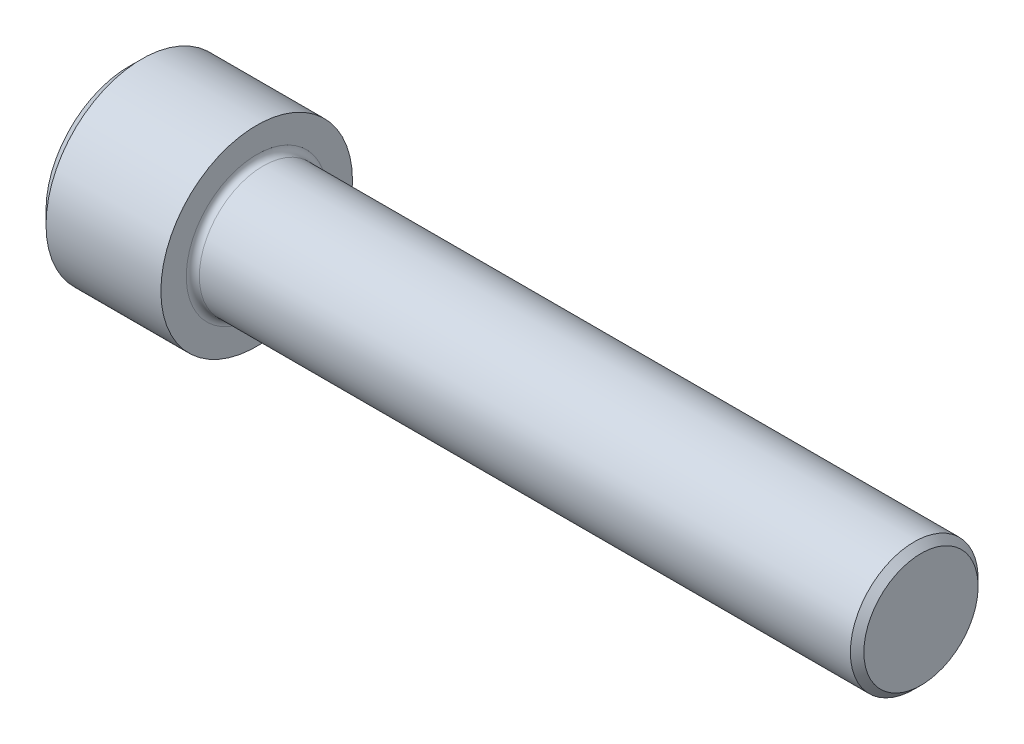
SolidWorks part; units mm, degrees
ref_plane "Plane1" through (0, 0, 0) normal (0, 0, 1) x (1, 0, 0)
ref_plane "Plane2" through (0, 0, 0) normal (0, 1, 0) x (1, 0, 0)
ref_plane "Plane3" through (0, 0, 0) normal (1, 0, 0) x (0, 0, -1)
sketch "BodySke" plane through (0, 0, 0) normal (0, 0, 1) x (1, 0, 0)
  line L0 (0, 0) -> (0, 10.3061)
  line L1 (1.6002, 11.9062) -> (15.875, 11.9062)
  line L2 (15.875, 11.9062) -> (15.875, 7.9375)
  line L3 (15.875, 7.9375) -> (97.5855, 7.9375)
  line L4 (98.425, 7.098) -> (98.425, 0)
  line L5 (98.425, 0) -> (0, 0)
  line L6 (-31.75, 0) -> (127, 0) construction
  line L7 (0, 10.3061) -> (1.6002, 11.9062)
  line L8 (98.425, 7.098) -> (97.5855, 7.9375)
  line L9 (0, -10.3061) -> (1.6002, -11.9063) construction
  line L10 (98.425, -7.098) -> (97.5855, -7.9375) construction
  line L11 (17.2847, 9.525) -> (17.2847, 3.175) construction
  line L12 (53.975, 9.525) -> (53.975, 3.175) construction
  line L13 (60.325, 9.525) -> (60.325, 3.175) construction
  dimension "Diameter" = 15.875
  dimension "Head_ht" = 15.875
  dimension "Length" = 82.55
  dimension "Body_ch_ang" = 45
  dimension "Head_dia" = 23.8125
  dimension "Head_ch_ang" = 45
  dimension "Head_side_ht" = 14.2748
  dimension "Minor_dia" = 14.1961
  dimension "Advance" = 1.4097
  dimension "Thread_nom" = 44.45
  dimension "Thread_length" = 38.1
revolve "Base-Revolve" add sketch "BodySke"
cosmetic thread "ThreadCosmetic" [suppressed]
fillet "Fillet1" radius 0.8128 1 edges at (15.875, 0, 7.9375)
sketch "Sketch2" plane through (0, 0, 0) normal (0, 0, 1) x (1, 0, 0)
  line L0 (0, 6.35) -> (7.7978, 6.35)
  line L1 (7.7978, 6.35) -> (11.464, 0)
  line L2 (-31.75, 0) -> (127, 0) construction
  line L3 (11.464, 0) -> (0, 0)
  line L4 (0, 0) -> (0, 6.35)
  line L5 (0, 10.3061) -> (0, -10.3061) construction
  line L6 (0, 0) -> (47.625, 0) construction
  line L7 (15.875, -11.9062) -> (15.875, 11.9062) construction
  dimension "D1" = 6.35
  dimension "D2" = 60
  dimension "Wall_thickness" = 8.0772
revolve "Hex-PreBroach" cut sketch "Sketch2" angle 360 about L6
sketch "Sketch3" plane through (0, 0, 0) normal (-1, 0, 0) x (0, 0.5, 0.866)
  line L0 (3.6662, 6.35) -> (-3.6662, 6.35)
  line L1 (-3.6662, 6.35) -> (-7.3323, 0)
  line L2 (3.6662, 6.35) -> (7.3323, 0)
  line L3 (3.6662, -6.35) -> (7.3323, 0)
  line L4 (3.6662, -6.35) -> (-3.6662, -6.35)
  line L5 (-3.6662, -6.35) -> (-7.3323, 0)
  dimension "D1" = 6.35
  dimension "D2" = 6.35
  dimension "Hex_size" = 12.7
extrude "Hex" cut sketch "Sketch3" against normal blind 7.7978
sketch "Sketch4" plane through (0, 0, 0) normal (-1, 0, 0) x (0, 0, 1)
  line L0 (0, 0) -> (7.6708, 0)
  line L1 (0, 0) -> (6.1484, 3.5498) construction
  line L2 (0, 0) -> (3.8354, 6.6431)
  line L3 (6.2649, 1.5933) -> (7.3437, 2.2162)
  line L4 (4.5123, 4.6289) -> (5.5911, 5.2517)
  arc A0 (6.2649, 1.5933) -> (4.5123, 4.6289) centre (0, 0) ccw
  arc A1 (7.6708, 0) -> (7.3437, 2.2162) centre (0, 0) ccw
  arc A2 (3.8354, 6.6431) -> (5.5911, 5.2517) centre (0, 0) cw
  dimension "D1" = 30
  dimension "Spline_n_dim" = 12.9286
  dimension "Spline_m_dim" = 15.3416
  dimension "D2" = 60
  dimension "D3" = 1.7526
  dimension "Spline_p_dim" = 3.5052
extrude "Spline" [suppressed] cut sketch "Sketch4" against normal blind 7.7978
pattern_circular "CirPattern1" [suppressed] count 6 every 60
sketch "Sketch5" plane through (0, 0, 0) normal (0, 0, 1) x (1, 0, 0)
  line L0 (-31.75, 0) -> (127, 0) construction
  line L2 (0, 10.3061) -> (0, -10.3061) construction
  circle A0 centre (5.0292, 0) radius 0.8065
  dimension "Drilled_hole_dia" = 1.6129
  dimension "Drilled_hole_loc" = 5.0292
extrude "Hole" [suppressed] cut sketch "Sketch5" against normal through all and the other way through all
pattern_circular "Drilled-4" [suppressed] count 2 every 60
pattern_circular "Drilled-6" [suppressed] count 3 every 60
sketch "ThdSchSke" plane through (0, 0, 0) normal (0, 0, 1) x (1, 0, 0)
  line L0 (53.975, -7.098) -> (53.3872, -7.9375)
  line L1 (53.975, -7.098) -> (54.5628, -7.9375)
  line L2 (54.5628, -7.9375) -> (54.5628, -9.9219)
  line L3 (-3.175, 0) -> (5.1513, 0) construction
  line L5 (54.5628, -9.9219) -> (53.3872, -9.9219)
  line L6 (53.3872, -9.9219) -> (53.3872, -7.9375)
  line L7 (0, 10.3061) -> (0, -10.3061) construction
  dimension "Thread_minor" = 14.1961
  dimension "Diameter" = 15.875
  dimension "Start" = 53.975
  dimension "SideAngle" = 55
  dimension "VeeAngle" = 70
  dimension "Overcut" = 19.8438
revolve "ThreadSchematic" [suppressed] cut sketch "ThdSchSke" angle 360 about L3
pattern_linear "ThdSchPat" [suppressed]
equation "\"D2@Sketch3\" = \"Hex_size@Sketch3\" / 2"
equation "\"D1@Sketch3\" = \"Hex_size@Sketch3\" / 2"
equation "\"D1@Sketch2\" = \"Hex_size@Sketch3\" / 2"
equation "\"D3@Sketch4\" = \"Spline_p_dim@Sketch4\" / 2"
equation "\"Thread_minor@ThreadCosmetic\"  =  \"Minor_dia@BodySke\""
equation "\"D2@CirPattern1\" = 360 / \"Num_teeth@CirPattern1\""
equation "\"Wall_thickness@Sketch2\" = \"Head_ht@BodySke\" - \"Key_eng@Hex\""
equation "\"Thread_length@ThreadCosmetic\" = ((sgn( (\"Length@BodySke\" - \"Advance@BodySke\" ) - \"Thread_nom@BodySke\" )-1)*( (\"Length@BodySke\" - \"Advance@BodySke\" ) - \"Thread_nom@BodySke\" ))/-2+ \"Thread_nom@BodySke\""
equation "\"Thread_minor@ThdSchSke\" = \"Minor_dia@BodySke\""
equation "\"Diameter@ThdSchSke\" = \"Diameter@BodySke\""
equation "\"Overcut@ThdSchSke\" = \"Diameter@BodySke\" * 1.25"
equation "\"Start@ThdSchSke\" = \"Head_ht@BodySke\" + \"Length@BodySke\" - \"Thread_length@ThreadCosmetic\"  '---Non-countersunk---"
equation "\"Num_threads@ThdSchPat\" = int( \"Thread_length@ThreadCosmetic\" / \"Advance@BodySke\" + 0.999 )  + 1"
equation "\"Advance@ThdSchPat\" = \"Thread_length@ThreadCosmetic\" /  (\"Num_threads@ThdSchPat\" - 1) 'relax it"
equation "\"Num_threads@ThdSchPat\" = \"Num_threads@ThdSchPat\" - sgn( \"Num_threads@ThdSchPat\" - 1) '---chamfered tips only---"
